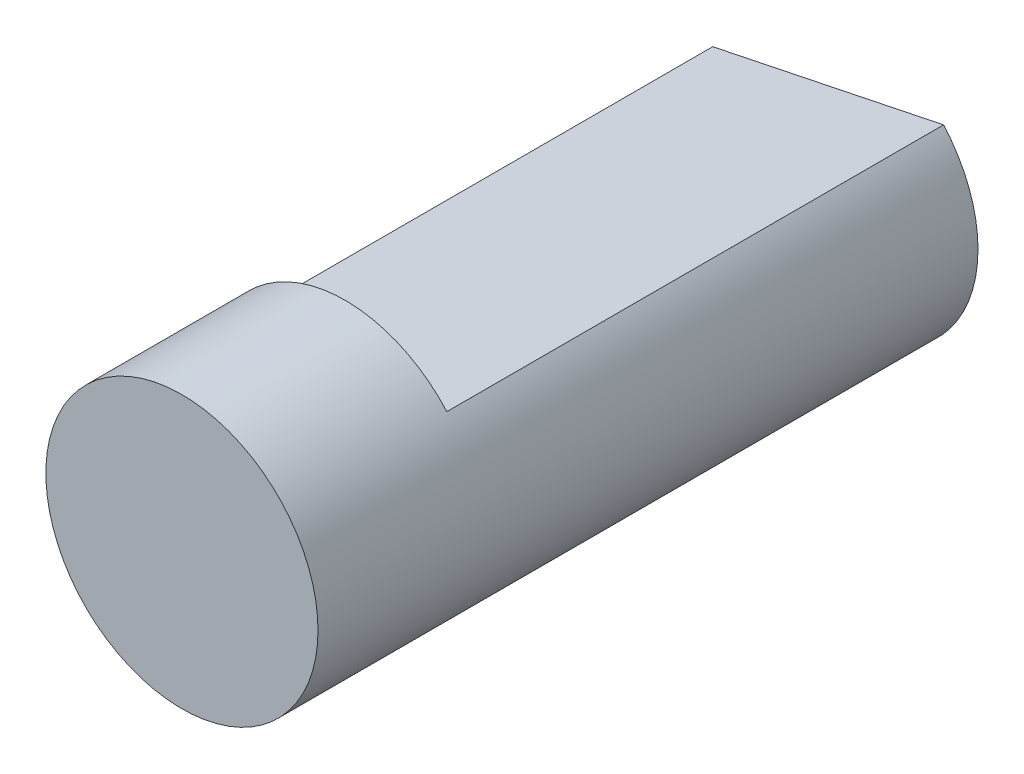
SolidWorks part; units mm, degrees
ref_plane "前视基准面" through (0, 0, 0) normal (0, 0, 1) x (1, 0, 0)
ref_plane "上视基准面" through (0, 0, 0) normal (0, 1, 0) x (1, 0, 0)
ref_plane "右视基准面" through (0, 0, 0) normal (1, 0, 0) x (0, 0, -1)
sketch "草图1" plane through (0, 0, 0) normal (0, 0, 1) x (1, 0, 0)
  circle A0 centre (0, 0) radius 2
  dimension "D1" = 4
extrude "凸台-拉伸1" add sketch "草图1" against normal blind 2.4
sketch "草图2" plane through (0, 0, -2.4) normal (0, 0, -1) x (-1, 0, 0)
  line L0 (1.8985, 0.6289) -> (-1.4939, 1.3297)
  circle A0 centre (0, 0) radius 2 construction
  circle A2 centre (0, 0) radius 2
  circle A3 centre (0, 0) radius 2
  circle M3 centre (0, 0) radius 2
  dimension "D2" = 1
  dimension "D1" = 0
extrude "凸台-拉伸2" add sketch "草图2" along normal blind 7.3 contours L0 M3
